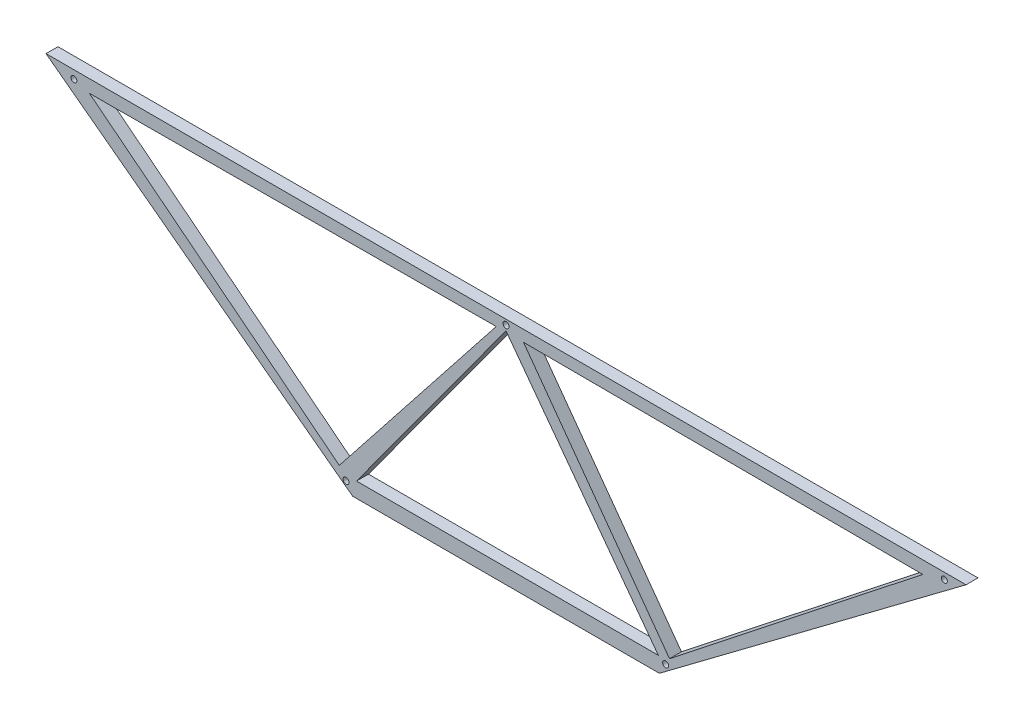
SolidWorks part; units mm, degrees
ref_plane "Front Plane" through (0, 0, 0) normal (0, 0, 1) x (1, 0, 0)
ref_plane "Top Plane" through (0, 0, 0) normal (0, 1, 0) x (1, 0, 0)
ref_plane "Right Plane" through (0, 0, 0) normal (1, 0, 0) x (0, 0, -1)
sketch "Sketch2" plane through (0, 0, 0) normal (0, 0, 1) x (1, 0, 0)
  line L0 (200, 0) -> (0, 0) construction
  line L1 (0, 0) -> (0, 284.871) construction
  line L2 (-200, 0) -> (200, 0)
  line L3 (200, 0) -> (600, 300)
  line L4 (600, 300) -> (-600, 300)
  line L5 (-600, 300) -> (-200, 0)
  dimension "D1" = 300
  dimension "D2" = 600
  dimension "D3" = 400
  dimension "D4" = 1200
extrude "Boss-Extrude2" add sketch "Sketch2" along normal blind 15.61
sketch "Sketch3" plane through (0, 0, 15.61) normal (0, 0, 1) x (1, 0, 0)
  line L0 (0, 0) -> (0, 300) construction
  line L1 (600, 300) -> (-600, 300) construction
  line L2 (0, 19.6783) -> (-195, 19.6783) construction
  line L6 (-195, 19.6783) -> (198.6873, 19.6783)
  line L7 (198.6873, 19.6783) -> (0, 286.7842)
  line L8 (0, 286.7842) -> (-195, 19.6783)
  dimension "D1" = 195
  dimension "D2" = 195
extrude "Cut-Extrude1" cut sketch "Sketch3" against normal through all
sketch "Sketch5" plane through (0, 0, 15.61) normal (0, 0, 1) x (1, 0, 0)
  line L0 (-600, 300) -> (-97.5, 153.2313) construction
  line L1 (0, 286.7842) -> (-195, 19.6783) construction
  line L2 (-97.5, 153.2313) -> (99.3437, 153.2313) construction
  line L3 (198.6873, 19.6783) -> (0, 286.7842) construction
  line L4 (99.3437, 153.2313) -> (600, 300) construction
  line L5 (-113.4304, 157.8842) -> (-223.918, 17.9385) construction
  line L6 (-600, 300) -> (-200, 0) construction
  line L7 (-217.4342, 26.151) -> (-12.8103, 285.3314)
  line L8 (-12.8103, 285.3314) -> (-543.3319, 283.4486)
  line L9 (-543.3319, 283.4486) -> (-217.4342, 26.151)
  line L10 (600, 300) -> (-600, 300) construction
  line L11 (-543.3319, 283.4486) -> (543.5399, 283.4486) construction
  line L12 (543.5399, 283.4486) -> (22.8527, 285.3314)
  line L13 (22.8527, 285.3314) -> (213.2365, 23.1587)
  line L14 (213.2365, 23.1587) -> (543.5399, 283.4486)
  line L16 (200, 0) -> (600, 300) construction
  point P20 (-278.0711, 284.39)
  point P21 (-380.3831, 154.7998)
  point P22 (118.0446, 154.2451)
  point P25 (378.3882, 153.3036)
  point P28 (283.1963, 284.39)
  dimension "D1" = 15.61
  dimension "D3" = 15.61
  dimension "D4" = 15.61
  dimension "D5" = 15.61
  dimension "D6" = 15.61
  dimension "D7" = 15.61
extrude "Cut-Extrude2" cut sketch "Sketch5" against normal through all
sketch "Sketch7" plane through (0, 0, 15.61) normal (0, 0, 1) x (1, 0, 0)
  line L0 (-600, 300) -> (-543.3319, 283.4486) construction
  line L1 (-543.3319, 283.4486) -> (-418.1628, 150) construction
  line L2 (-217.4342, 26.151) -> (-200, 0) construction
  line L3 (-200, 0) -> (-195, 19.6783) construction
  line L4 (-195, 19.6783) -> (-217.4342, 26.151) construction
  line L5 (-217.4342, 26.151) -> (-569.3818, 277.0364) construction
  line L6 (-600, 300) -> (-200, 0) construction
  line L7 (-12.8103, 285.3314) -> (0, 300) construction
  line L8 (600, 300) -> (-600, 300) construction
  line L9 (0, 300) -> (22.8527, 285.3314) construction
  line L10 (22.8527, 285.3314) -> (0, 286.7842) construction
  line L11 (0, 286.7842) -> (-12.8103, 285.3314) construction
  line L12 (0, 286.7842) -> (0, 300) construction
  line L13 (600, 300) -> (543.5399, 283.4486) construction
  line L14 (200, 0) -> (213.2365, 23.1587) construction
  line L15 (213.2365, 23.1587) -> (198.6873, 19.6783) construction
  line L16 (198.6873, 19.6783) -> (208.1545, 14.2672) construction
  line L17 (-195, 19.6783) -> (-208.7171, 13.0755) construction
  circle A0 centre (-563.627, 289.3763) radius 3.9
  circle A1 centre (0, 293.3921) radius 3.9
  circle A2 centre (571.7699, 291.7243) radius 3.9
  circle A3 centre (208.1545, 14.2672) radius 3.9
  circle A4 centre (-208.7171, 13.0755) radius 3.9
  dimension "D1" = 7.8
  dimension "D2" = 7.8
  dimension "D3" = 7.8
  dimension "D4" = 7.8
  dimension "D5" = 7.8
extrude "Cut-Extrude3" cut sketch "Sketch7" against normal through all
